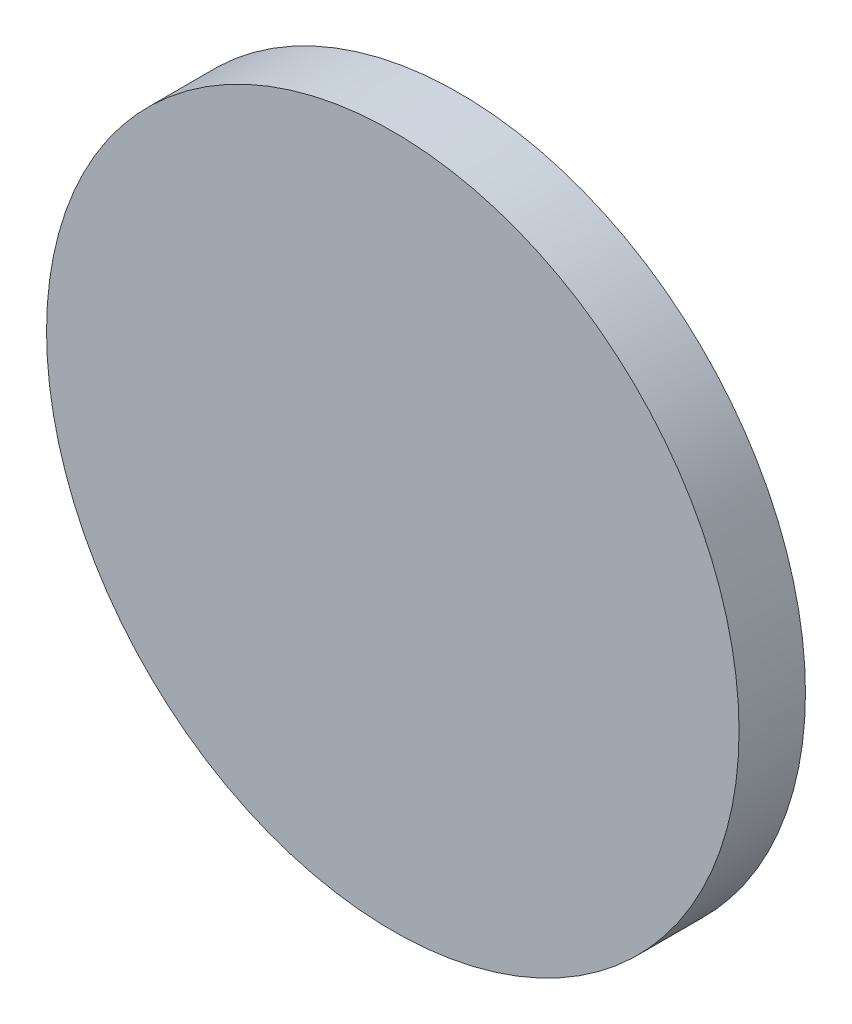
SolidWorks part; units mm, degrees
ref_plane "Plano frontal" through (0, 0, 0) normal (0, 0, 1) x (1, 0, 0)
ref_plane "Plano superior" through (0, 0, 0) normal (0, 1, 0) x (1, 0, 0)
ref_plane "Plano direito" through (0, 0, 0) normal (1, 0, 0) x (0, 0, -1)
sketch "Sketch1" plane through (0, 0, 0) normal (0, 0, 1) x (1, 0, 0)
  circle A0 centre (0, 0) radius 182.5
  dimension "D1" = 365
extrude "Boss-Extrude1" add sketch "Sketch1" along normal blind 35
